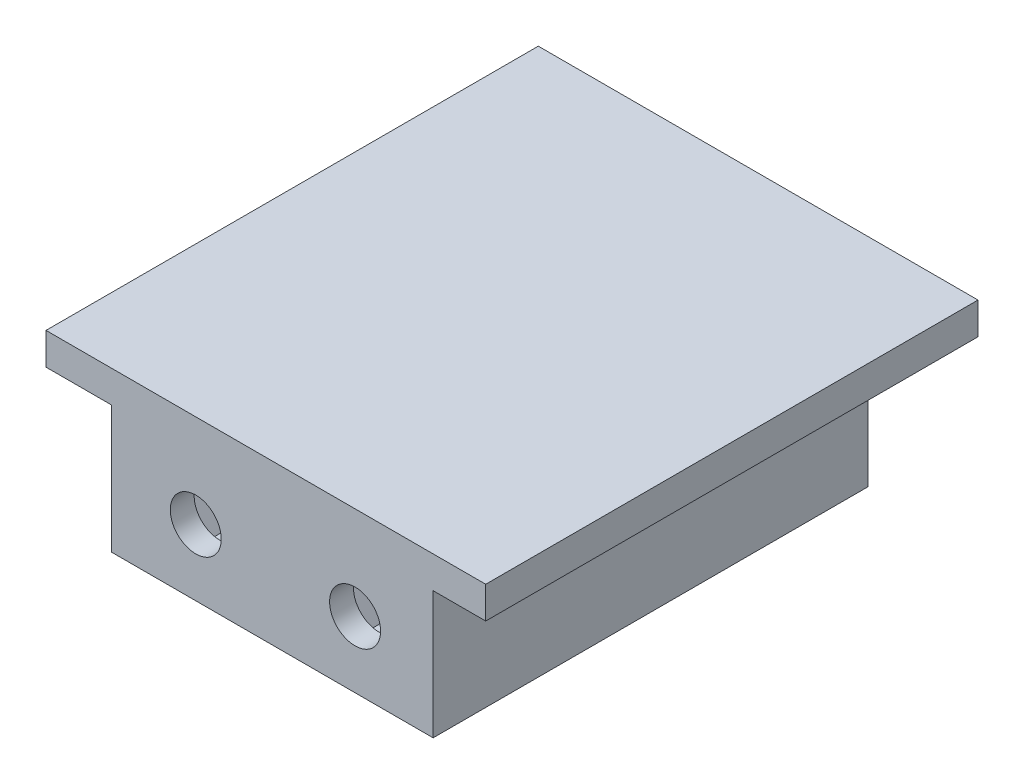
SolidWorks part; units mm, degrees
ref_plane "Front Plane" through (0, 0, 0) normal (0, 0, 1) x (1, 0, 0)
ref_plane "Top Plane" through (0, 0, 0) normal (0, 1, 0) x (1, 0, 0)
ref_plane "Right Plane" through (0, 0, 0) normal (1, 0, 0) x (0, 0, -1)
sketch "Sketch1" plane through (0, 0, 0) normal (0, 1, 0) x (1, 0, 0)
  line L1 (11.8589, 17.0866) -> (39.4589, 17.0866)
  line L2 (11.8589, 17.0866) -> (11.8589, -13.8134)
  line L3 (11.8589, -13.8134) -> (39.4589, -13.8134)
  line L4 (39.4589, 17.0866) -> (39.4589, -13.8134)
  dimension "D1" = 30.9
  dimension "D2" = 27.6
extrude "Boss-Extrude1" add sketch "Sketch1" along normal blind 2
sketch "Sketch2" plane through (0, 0, 0) normal (0, -1, 0) x (1, 0, 0)
  line L0 (11.8589, 13.8134) -> (39.4589, 13.8134) construction
  line L1 (15.9589, 13.8134) -> (36.1589, 13.8134)
  line L2 (15.9589, 13.8134) -> (15.9589, -13.4866)
  line L3 (15.9589, -13.4866) -> (36.1589, -13.4866)
  line L4 (36.1589, 13.8134) -> (36.1589, -13.4866)
  line L5 (39.4589, -17.0866) -> (11.8589, -17.0866) construction
  line L7 (11.8589, -17.0866) -> (11.8589, 13.8134) construction
  line L9 (39.4589, 13.8134) -> (39.4589, -17.0866) construction
  dimension "D1" = 3.6
  dimension "D2" = 3.3
  dimension "D3" = 4.1
extrude "Boss-Extrude2" add sketch "Sketch2" along normal blind 8
sketch "Sketch3" plane through (0, 0, 13.8134) normal (0, 0, 1) x (1, 0, 0)
  circle A0 centre (21.2589, -3.85) radius 1.6
  circle A1 centre (31.2589, -3.85) radius 1.6
  dimension "D1" = 3.2
  dimension "D2" = 3.2
extrude "Cut-Extrude1" cut sketch "Sketch3" against normal blind 32
ref_plane "Plane1" through (0, 0, 12.3134) normal (0, 0, 1) x (1, 0, 0)
sketch "Sketch4" plane through (0, 0, 12.3134) normal (0, 0, 1) x (1, 0, 0)
  line L1 (32.8755, -6.65) -> (34.492, -3.85)
  line L2 (34.492, -3.85) -> (32.8755, -1.05)
  line L3 (32.8755, -1.05) -> (29.6423, -1.05)
  line L4 (29.6423, -1.05) -> (28.0257, -3.85)
  line L5 (28.0257, -3.85) -> (29.6423, -6.65)
  line L6 (29.6423, -6.65) -> (32.8755, -6.65)
  line L7 (22.92, -6.6238) -> (24.4916, -3.7984)
  line L8 (24.4916, -3.7984) -> (22.8305, -1.0245)
  line L9 (22.8305, -1.0245) -> (19.5978, -1.0762)
  line L10 (19.5978, -1.0762) -> (18.0261, -3.9016)
  line L11 (18.0261, -3.9016) -> (19.6872, -6.6755)
  line L12 (19.6872, -6.6755) -> (22.92, -6.6238)
  circle A0 centre (31.2589, -3.85) radius 2.8 construction
  circle A1 centre (21.2589, -3.85) radius 2.8 construction
extrude "Cut-Extrude2" cut sketch "Sketch4" against normal blind 2.5
ref_plane "Plane2" through (0, 0, -11.9866) normal (0, 0, -1) x (-1, 0, 0)
sketch "Sketch5" plane through (0, 0, -11.9866) normal (0, 0, -1) x (-1, 0, 0)
  line L1 (-29.6423, -6.65) -> (-28.0257, -3.85)
  line L2 (-28.0257, -3.85) -> (-29.6423, -1.05)
  line L3 (-29.6423, -1.05) -> (-32.8755, -1.05)
  line L4 (-32.8755, -1.05) -> (-34.492, -3.85)
  line L5 (-34.492, -3.85) -> (-32.8755, -6.65)
  line L6 (-32.8755, -6.65) -> (-29.6423, -6.65)
  line L7 (-19.6423, -6.65) -> (-18.0257, -3.85)
  line L8 (-18.0257, -3.85) -> (-19.6423, -1.05)
  line L9 (-19.6423, -1.05) -> (-22.8755, -1.05)
  line L10 (-22.8755, -1.05) -> (-24.492, -3.85)
  line L11 (-24.492, -3.85) -> (-22.8755, -6.65)
  line L12 (-22.8755, -6.65) -> (-19.6423, -6.65)
  circle A0 centre (-31.2589, -3.85) radius 2.8 construction
  circle A1 centre (-21.2589, -3.85) radius 2.8 construction
extrude "Cut-Extrude3" cut sketch "Sketch5" against normal blind 2.5
